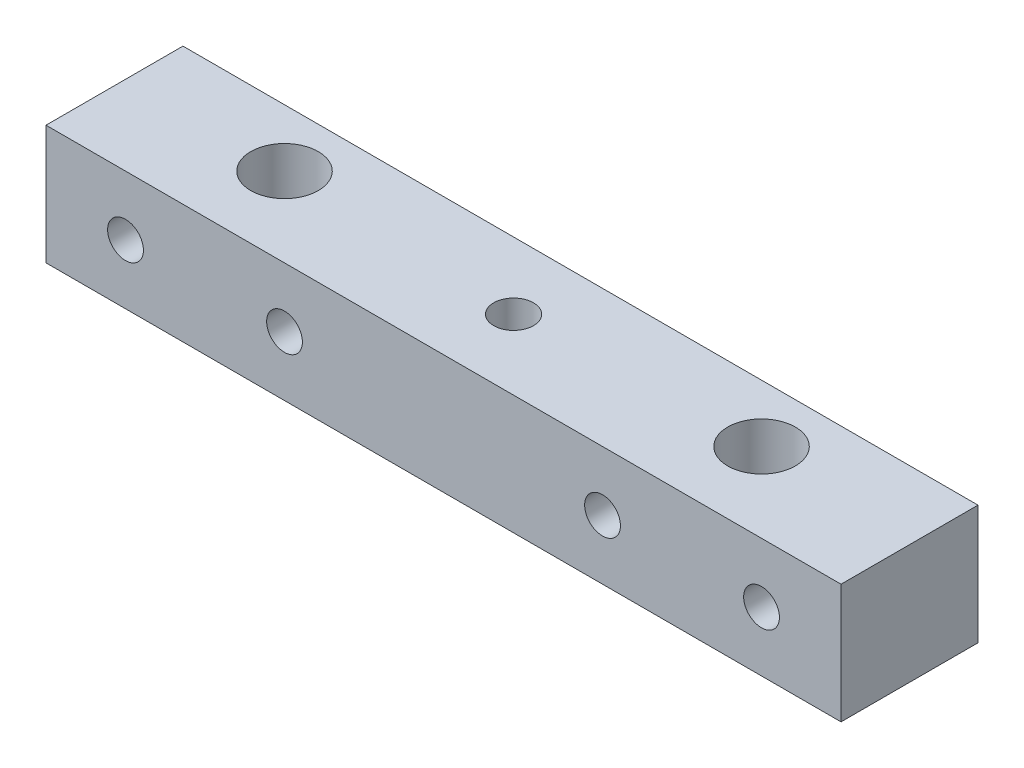
SolidWorks part; units mm, degrees
ref_plane "Front Plane" through (0, 0, 0) normal (0, 0, 1) x (1, 0, 0)
ref_plane "Top Plane" through (0, 0, 0) normal (0, 1, 0) x (1, 0, 0)
ref_plane "Right Plane" through (0, 0, 0) normal (1, 0, 0) x (0, 0, -1)
sketch "Sketch1" plane through (0, 0, 0) normal (0, 1, 0) x (1, 0, 0)
  line L1 (-50, -8.614) -> (50, -8.614)
  line L2 (-50, -8.614) -> (-50, 8.614)
  line L3 (-50, 8.614) -> (50, 8.614)
  line L4 (50, -8.614) -> (50, 8.614)
  line L5 (-50, -8.614) -> (50, 8.614) construction
  line L6 (-50, 8.614) -> (50, -8.614) construction
  point P0 (0, 0)
  dimension "D1" = 17.228
  dimension "D2" = 100
extrude "Boss-Extrude1" add sketch "Sketch1" along normal blind 15
hole_wizard "CBORE for M5 Hex Head Bolt1" positions "Sketch2" profile "Sketch3" counterbore size "M5" standard "ANSI Metric" end condition through all
sketch "Sketch2" plane through (0, 15, 0) normal (0, 1, 0) x (1, 0, 0)
  line L0 (-30, 1.386) -> (30, 1.386)
  line L2 (-50, -8.614) -> (50, -8.614) construction
  point P0 (-30, 1.386)
  point P1 (30, 1.386)
  point P12 (0, 1.386)
  dimension "D1" = 10
  dimension "D2" = 60
sketch "Sketch3" plane through (-30, 15, -1.386) normal (1, 0, 0) x (0, 0, 1)
  line L0 (0, 0) -> (0, 15)
  line L1 (0, 15) -> (2.25, 15)
  line L3 (2.25, 15) -> (2.25, 6)
  line L4 (2.25, 6) -> (4.25, 6)
  line L5 (4.25, 6) -> (4.25, 0)
  line L7 (4.25, 0) -> (0, 0)
  line L11 (0, -6.35) -> (0, 107.95) construction
  dimension "Thru Hole Dia." = 4.5
  dimension "Thru Hole Depth" = 15
  dimension "C'Bore Dia." = 8.5
  dimension "C'Bore Depth" = 6
hole_wizard "M4 Clearance Hole1" positions "Sketch6" profile "Sketch7" hole size "M4" standard "ANSI Metric" end condition through all
sketch "Sketch6" plane through (0, 0, 8.614) normal (0, 0, 1) x (1, 0, 0)
  line L0 (-20, 7.5) -> (20, 7.5)
  line L2 (-40, 7.5) -> (40, 7.5)
  line L3 (-50, 0) -> (50, 0) construction
  point P1 (-20, 7.5)
  point P2 (20, 7.5)
  point P5 (-40, 7.5)
  point P14 (40, 7.5)
  point P17 (0, 0)
  point P18 (0, 7.5)
  point P19 (0, 7.5)
  dimension "D1" = 80
  dimension "D2" = 40
  dimension "D3" = 7.5
sketch "Sketch7" plane through (-20, 7.5, 8.614) normal (1, 0, 0) x (0, -1, 0)
  line L0 (0, 0) -> (0, 17.228)
  line L1 (0, 17.228) -> (2.25, 17.228)
  line L2 (2.25, 17.228) -> (2.25, 0)
  line L5 (2.25, 0) -> (0, 0)
  line L11 (0, -6.35) -> (0, 107.95) construction
  dimension "Thru Hole Dia." = 4.5
  dimension "Thru Hole Depth" = 17.228
hole_wizard "CBORE for M5 Hex Head Bolt2" positions "Sketch9" profile "Sketch11" counterbore size "M5" standard "ANSI Metric" end condition through all
sketch "Sketch9" plane through (0, 15, 0) normal (0, 1, 0) x (1, 0, 0)
  point P0 (0, 0.2)
  dimension "D1" = 0.2
sketch "Sketch11" plane through (0, 15, -0.2) normal (1, 0, 0) x (0, 0, 1)
  line L0 (0, 0) -> (0, 15)
  line L1 (0, 15) -> (2.25, 15)
  line L3 (2.25, 15) -> (2.25, 4.2)
  line L4 (2.25, 4.2) -> (2.5, 4.2)
  line L5 (2.5, 4.2) -> (2.5, 0)
  line L7 (2.5, 0) -> (0, 0)
  line L11 (0, -6.35) -> (0, 107.95) construction
  dimension "Thru Hole Dia." = 4.5
  dimension "Thru Hole Depth" = 15
  dimension "C'Bore Dia." = 5
  dimension "C'Bore Depth" = 4.2
